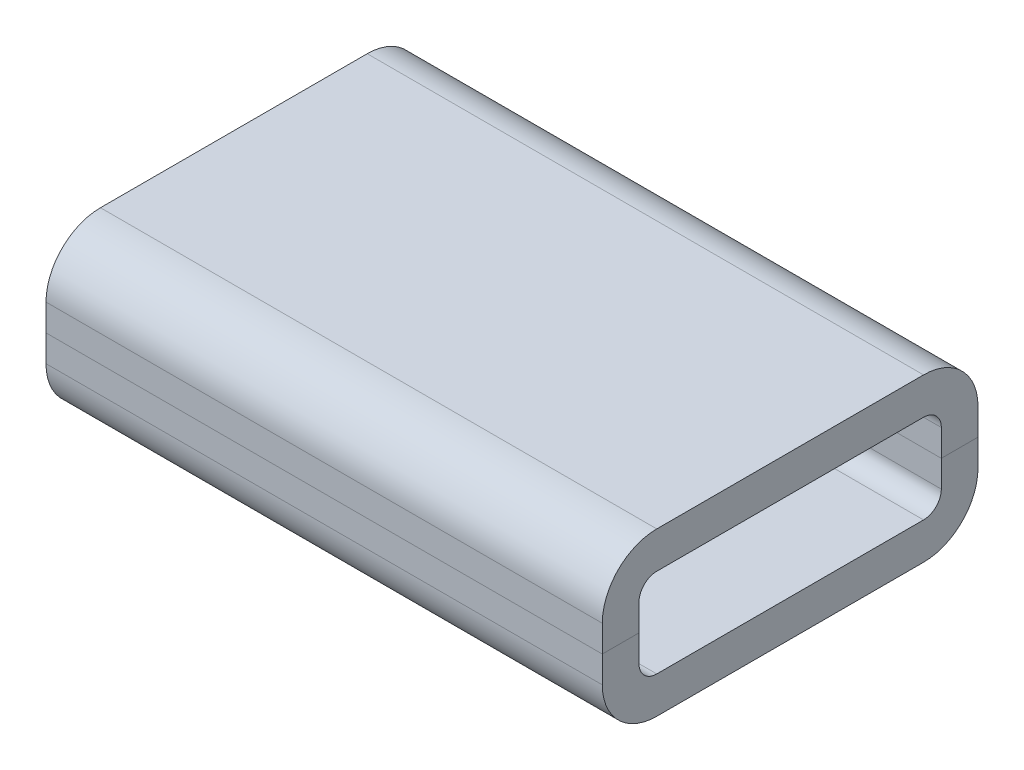
SolidWorks part; units mm, degrees
material "Copper"
ref_plane "Front Plane" through (0, 0, 0) normal (0, 0, 1) x (1, 0, 0)
ref_plane "Top Plane" through (0, 0, 0) normal (0, 1, 0) x (1, 0, 0)
ref_plane "Right Plane" through (0, 0, 0) normal (1, 0, 0) x (0, 0, -1)
sketch "Sketch1" plane through (0, 0, 0) normal (1, 0, 0) x (0, 0, -1)
  line L1 (-13.6, 0) -> (-13.6, 2.4)
  line L2 (-12, 4) -> (12, 4)
  line L3 (13.6, 2.4) -> (13.6, 0)
  line L4 (13.6, 0) -> (16.9, 0)
  line L5 (16.9, 0) -> (16.9, 2.4)
  line L6 (12, 7.3) -> (-12, 7.3)
  line L7 (-13.6, 0) -> (-16.9, 0)
  line L8 (-16.9, 0) -> (-16.9, 2.4)
  arc A1 (-13.6, 2.4) -> (-12, 4) centre (-12, 2.4) cw
  arc A2 (12, 4) -> (13.6, 2.4) centre (12, 2.4) cw
  arc A3 (16.9, 2.4) -> (12, 7.3) centre (12, 2.4) ccw
  arc A4 (-12, 7.3) -> (-16.9, 2.4) centre (-12, 2.4) ccw
  point P7 (0, 4)
  dimension "D1" = 1.6
  dimension "D5" = 4.9
  dimension "D2" = 24
  dimension "D3" = 3.3
  dimension "D4" = 3.3
  dimension "D6" = 2.4
extrude "Boss-Extrude1" add sketch "Sketch1" along normal mid plane 50.05
mirror "Mirror1" about plane through (0, 0, 0) normal (0, 1, 0) of bodies 101
equation "\"D5@Sketch1\"=\"D1@Sketch1\"+\"D3@Sketch1\""
